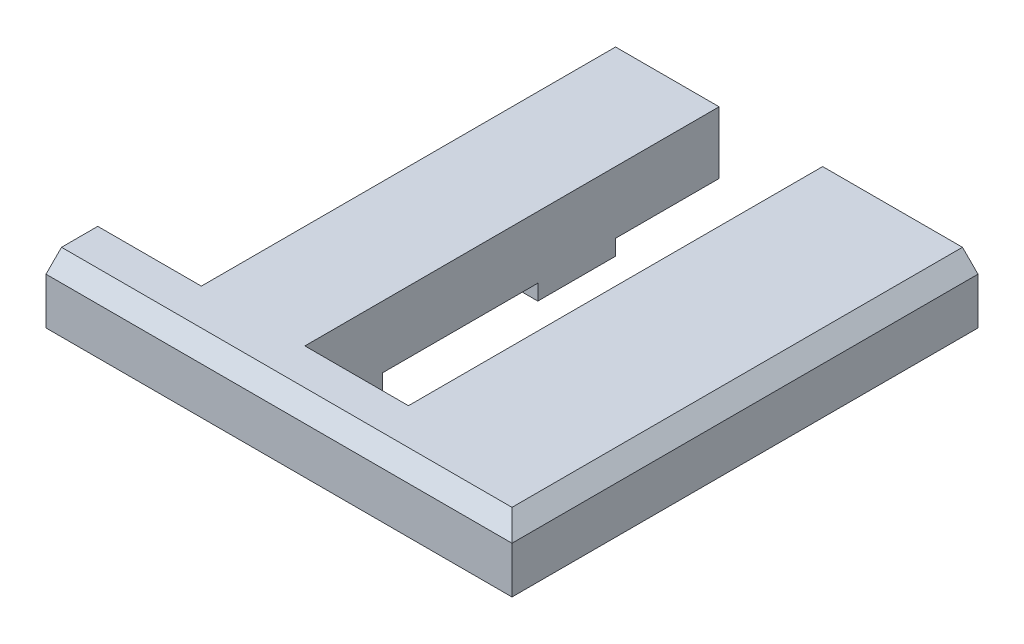
SolidWorks part; units mm, degrees
ref_plane "Front Plane" through (0, 0, 0) normal (0, 0, 1) x (1, 0, 0)
ref_plane "Top Plane" through (0, 0, 0) normal (0, 1, 0) x (1, 0, 0)
ref_plane "Right Plane" through (0, 0, 0) normal (1, 0, 0) x (0, 0, -1)
sketch "Sketch1" plane through (0, 0, 0) normal (0, 1, 0) x (1, 0, 0)
  line L0 (-25.4, 25.4) -> (-228.6, 25.4)
  line L1 (0, 0) -> (-228.6, 0)
  line L2 (0, 0) -> (0, 228.6)
  line L3 (0, 228.6) -> (-228.6, 228.6)
  line L4 (-228.6, 0) -> (-228.6, 228.6)
  line L5 (-25.4, 25.4) -> (-25.4, 228.6)
  line L6 (-76.2, 25.4) -> (-76.2, 228.6)
  line L7 (-127, 25.4) -> (-127, 228.6)
  line L8 (-177.8, 25.4) -> (-177.8, 228.6)
  dimension "D1" = 228.6
  dimension "D2" = 228.6
  dimension "D3" = 25.4
  dimension "D4" = 50.8
  dimension "D5" = 50.8
  dimension "D6" = 50.8
extrude "Boss-Extrude1" add sketch "Sketch1" along normal blind 38.1 contours L5 L0 L4 L1 L2 L3 | L6 L0 L5 L3 | L8 L0 L7 L3
sketch "Sketch3" plane through (-228.6, 0, 0) normal (-1, 0, 0) x (0, 0, 1)
  circle A0 centre (-12.7, 19.05) radius 9.525
  dimension "D1" = 19.05
extrude "Cut-Extrude1" cut sketch "Sketch3" against normal blind 38.1
sketch "Sketch4" plane through (0, 0, -228.6) normal (0, 0, -1) x (-1, 0, 0)
  circle A0 centre (12.6849, 19.05) radius 9.525
  dimension "D1" = 19.05
extrude "Cut-Extrude2" cut sketch "Sketch4" against normal blind 38.1
sketch "Sketch5" plane through (0, 0, 0) normal (0, -1, 0) x (-1, 0, 0)
  line L0 (50.8, 431.7421) -> (50.8, 177.7421)
  line L1 (50.8, 431.7421) -> (279.4, 431.771)
  line L2 (228.6, 431.771) -> (330.2, 431.771) construction
  line L3 (279.4, 431.771) -> (279.4, 177.7421)
  line L4 (279.4, 177.7421) -> (50.8, 177.7421)
  dimension "D1" = 254
extrude "Cut-Extrude3" cut sketch "Sketch5" against normal blind 7.62
sketch "Sketch6" plane through (0, 0, 0) normal (0, -1, 0) x (-1, 0, 0)
  line L0 (177.8, 63.471) -> (177.8, 139.671)
  line L1 (177.8, 25.4) -> (177.8, 177.7421) construction
  line L7 (177.8, 139.671) -> (50.8, 139.671)
  line L9 (177.8, 63.471) -> (50.8, 63.471)
  line L10 (50.8, 139.671) -> (50.8, 63.471)
  dimension "D1" = 76.2
extrude "Cut-Extrude4" cut sketch "Sketch6" against normal blind 7.62
chamfer "Chamfer1" distance 7.62 angle 45 4 edges at (-114.3, 0, 0) (-114.3, 38.1, 0) (0, 0, -114.3) (0, 38.1, -114.3)
